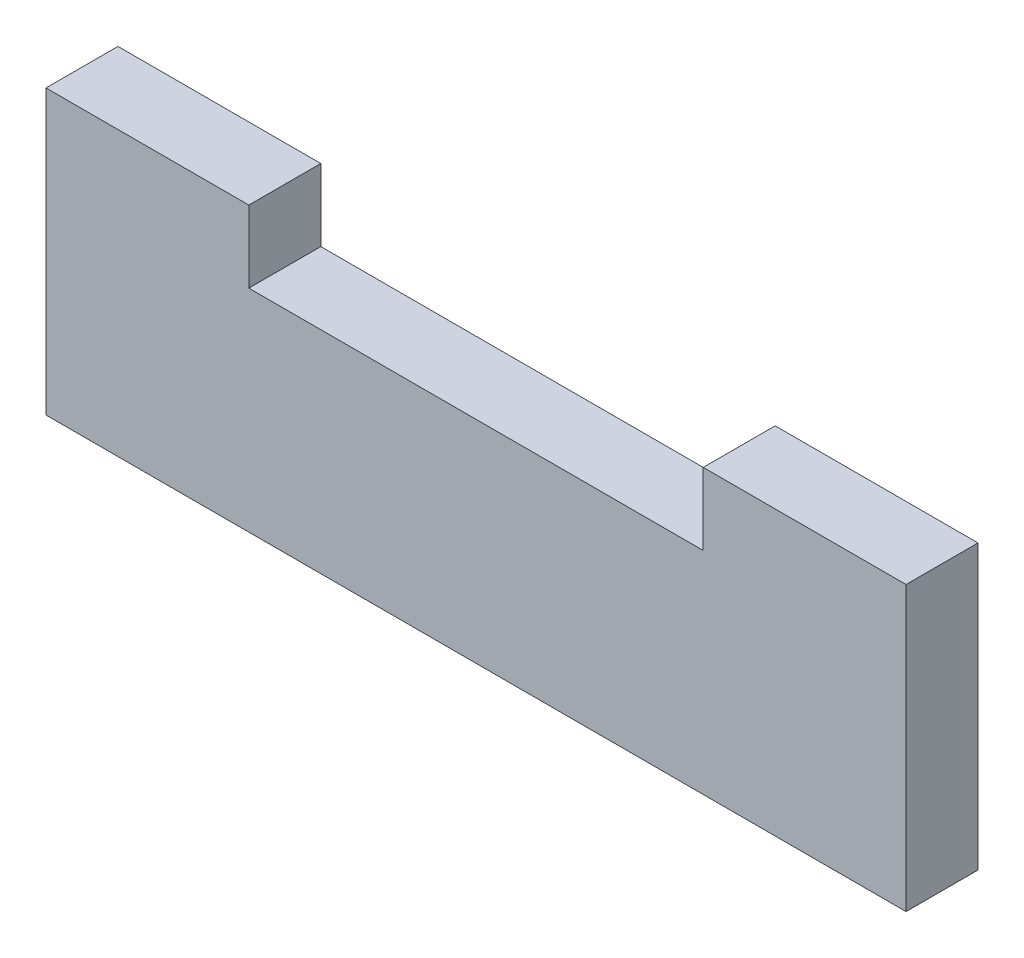
SolidWorks part; units mm, degrees
ref_plane "Front Plane" through (0, 0, 0) normal (0, 0, 1) x (1, 0, 0)
ref_plane "Top Plane" through (0, 0, 0) normal (0, 1, 0) x (1, 0, 0)
ref_plane "Right Plane" through (0, 0, 0) normal (1, 0, 0) x (0, 0, -1)
sketch "Sketch1" plane through (0, 0, 0) normal (0, 0, 1) x (1, 0, 0)
  line L0 (-37.95, 0) -> (37.95, 0)
  line L1 (37.95, 0) -> (37.95, 25)
  line L2 (37.95, 25) -> (20.05, 25)
  line L3 (20.05, 25) -> (20.05, 18.65)
  line L4 (20.05, 18.65) -> (-20.05, 18.65)
  line L5 (-20.05, 18.65) -> (-20.05, 25)
  line L6 (-20.05, 25) -> (-37.95, 25)
  line L7 (-37.95, 25) -> (-37.95, 0)
  point P8 (0, 0)
  dimension "D1" = 17.9
  dimension "D2" = 6.35
  dimension "D3" = 25
  dimension "D4" = 40.1
extrude "Boss-Extrude1" add sketch "Sketch1" along normal blind 6.35
